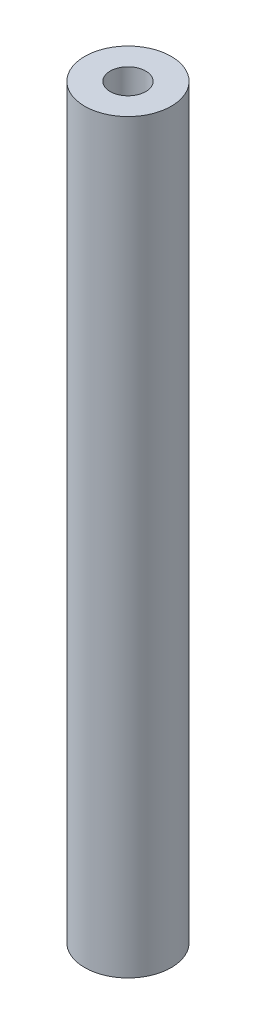
SolidWorks part; units mm, degrees
ref_plane "Front Plane" through (0, 0, 0) normal (0, 0, 1) x (1, 0, 0)
ref_plane "Top Plane" through (0, 0, 0) normal (0, 1, 0) x (1, 0, 0)
ref_plane "Right Plane" through (0, 0, 0) normal (1, 0, 0) x (0, 0, -1)
sketch "Sketch1" plane through (0, 0, 0) normal (0, 1, 0) x (1, 0, 0)
  circle A0 centre (0, 0) radius 12.75
extrude "Boss-Extrude1" add sketch "Sketch1" along normal blind 220
sketch "Sketch2" plane through (0, 0, 0) normal (0, 1, 0) x (1, 0, 0)
  circle A0 centre (0, 0) radius 5.25
extrude "Cut-Extrude1" cut sketch "Sketch2" against normal through all both and the other way through all contours A0
